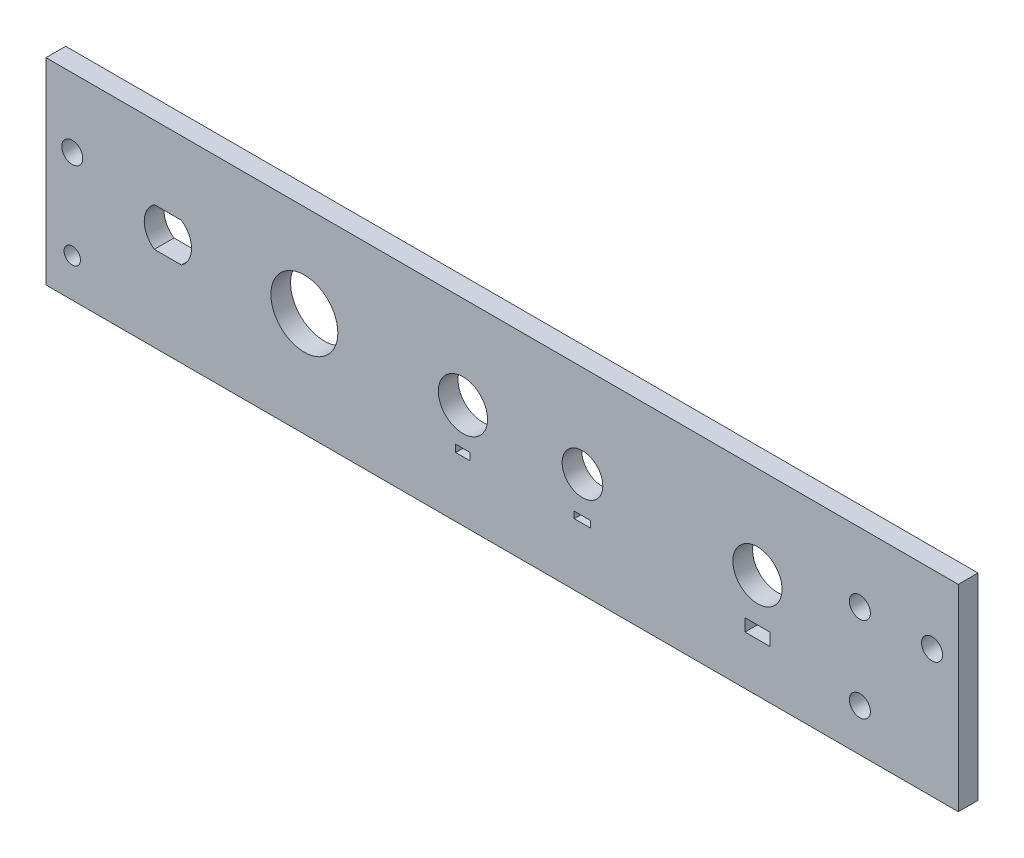
SolidWorks part; units mm, degrees
ref_plane "Front Plane" through (0, 0, 0) normal (0, 0, 1) x (1, 0, 0)
ref_plane "Top Plane" through (0, 0, 0) normal (0, 1, 0) x (1, 0, 0)
ref_plane "Right Plane" through (0, 0, 0) normal (1, 0, 0) x (0, 0, -1)
sketch "Sketch1" plane through (0, 0, 0) normal (0, 0, 1) x (1, 0, 0)
  line L0 (0, 0) -> (139, 0)
  line L2 (0, 0) -> (0, 30)
  line L3 (0, 30) -> (139, 30)
  line L4 (139, 0) -> (139, 30)
  line L5 (69.5, 30) -> (69.5, 0) construction
  line L17 (81.7309, 15.9065) -> (81.7309, 9.9065) construction
  line L30 (63.5225, 15.9065) -> (63.5225, 9.6565) construction
  line L31 (62.4225, 9.1065) -> (64.6225, 9.1065)
  line L43 (62.4225, 9.1065) -> (62.4225, 10.2065)
  line L44 (62.4225, 10.2065) -> (64.6225, 10.2065)
  line L45 (64.6225, 9.1065) -> (64.6225, 10.2065)
  line L50 (62.4225, 9.1065) -> (64.6225, 10.2065) construction
  line L51 (62.4225, 10.2065) -> (64.6225, 9.1065) construction
  line L58 (80.4809, 9.4065) -> (82.9809, 9.4065)
  line L59 (80.4809, 9.4065) -> (80.4809, 10.4065)
  line L64 (80.4809, 10.4065) -> (82.9809, 10.4065)
  line L65 (82.9809, 9.4065) -> (82.9809, 10.4065)
  line L66 (80.4809, 9.4065) -> (82.9809, 10.4065) construction
  line L71 (80.4809, 10.4065) -> (82.9809, 9.4065) construction
  line L72 (106.4997, 7.4565) -> (110.2997, 7.4565)
  line L77 (106.4997, 7.4565) -> (106.4997, 9.3565)
  line L78 (106.4997, 9.3565) -> (110.2997, 9.3565)
  line L79 (16.5053, 12.9565) -> (20.632, 12.9565)
  line L80 (20.632, 18.8565) -> (16.5053, 18.8565)
  line L81 (110.2997, 7.4565) -> (110.2997, 9.3565)
  line L82 (106.4997, 7.4565) -> (110.2997, 9.3565) construction
  line L83 (106.4997, 9.3565) -> (110.2997, 7.4565) construction
  circle A4 centre (4, 19.5) radius 1.6
  circle A5 centre (135, 19.5) radius 1.6
  circle A11 centre (124, 19.5) radius 1.6
  arc A21 (16.5053, 18.8565) -> (16.5053, 12.9565) centre (18.5687, 15.9065) ccw
  arc A22 (20.632, 12.9565) -> (20.632, 18.8565) centre (18.5687, 15.9065) ccw
  circle A23 centre (18.5687, 15.9065) radius 3.6 construction
  circle A26 centre (135, -46.5) radius 1.6 [skipped]
  circle A27 centre (4, -46.5) radius 1.6 [skipped]
  circle A28 centre (39.3612, 15.9065) radius 5.1
  circle A29 centre (63.5225, 15.9065) radius 3.75
  circle A30 centre (81.7309, 15.9065) radius 3.1
  circle A31 centre (108.3997, 15.9065) radius 3.75
  circle A32 centre (4, 5.8958) radius 1.25
  circle A34 centre (124, 6.5) radius 1.6
  point P19 (63.5225, 9.6565)
  point P27 (81.7309, 9.9065)
  point P43 (108.3997, 8.4065)
  dimension "D3" = 10.2
  dimension "D4" = 2.2
  dimension "D5" = 1.1
  dimension "D8" = 3.2
  dimension "D24" = 2.5
  dimension "D25" = 13
  dimension "D19" = 7.5
  dimension "D6" = 7.5
  dimension "D21" = 3.8
  dimension "D17" = 7.2
  dimension "D1" = 139
  dimension "D2" = 30
  dimension "D7" = 5.7
  dimension "D11" = 131
  dimension "D12" = 4
  dimension "D13" = 10.5
  dimension "D14" = 1
  dimension "D15" = 6
  dimension "D16" = 5.9
  dimension "D18" = 15
  dimension "D20" = 4
  dimension "D22" = 1.9
  dimension "D23" = 7.5
  dimension "D9" = 2
  dimension "D10" = 2
extrude "Boss-Extrude1" add sketch "Sketch1" along normal blind 3
